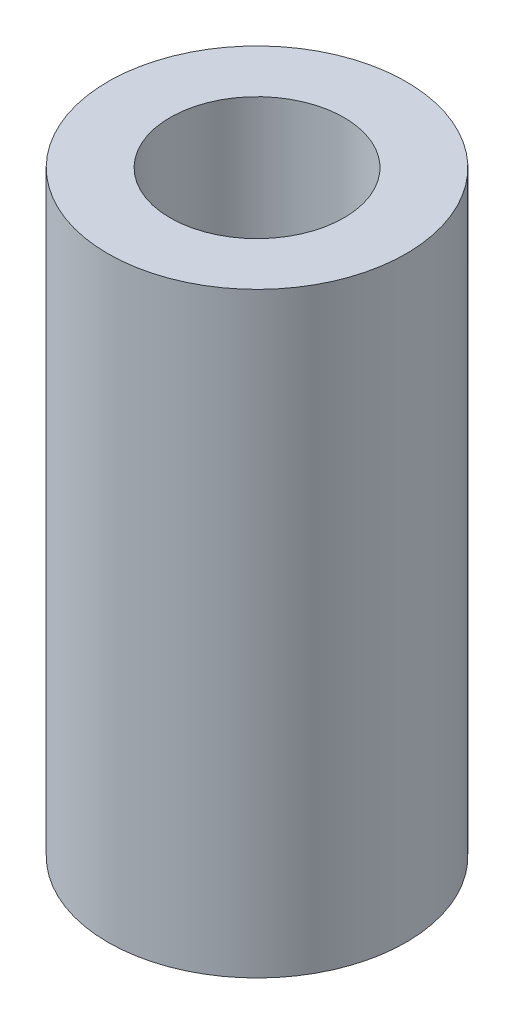
SolidWorks part; units mm, degrees
ref_plane "Front" through (0, 0, 0) normal (0, 0, 1) x (1, 0, 0)
ref_plane "Top" through (0, 0, 0) normal (0, 1, 0) x (1, 0, 0)
ref_plane "Right" through (0, 0, 0) normal (1, 0, 0) x (0, 0, -1)
sketch "Sketch1" plane through (0, 0, 0) normal (0, 1, 0) x (1, 0, 0)
  circle A0 centre (0, 0) radius 1.75
  circle A1 centre (0, 0) radius 3
  dimension "D1" = 3.5
  dimension "D2" = 6
extrude "Boss-Extrude1" add sketch "Sketch1" along normal blind 12
